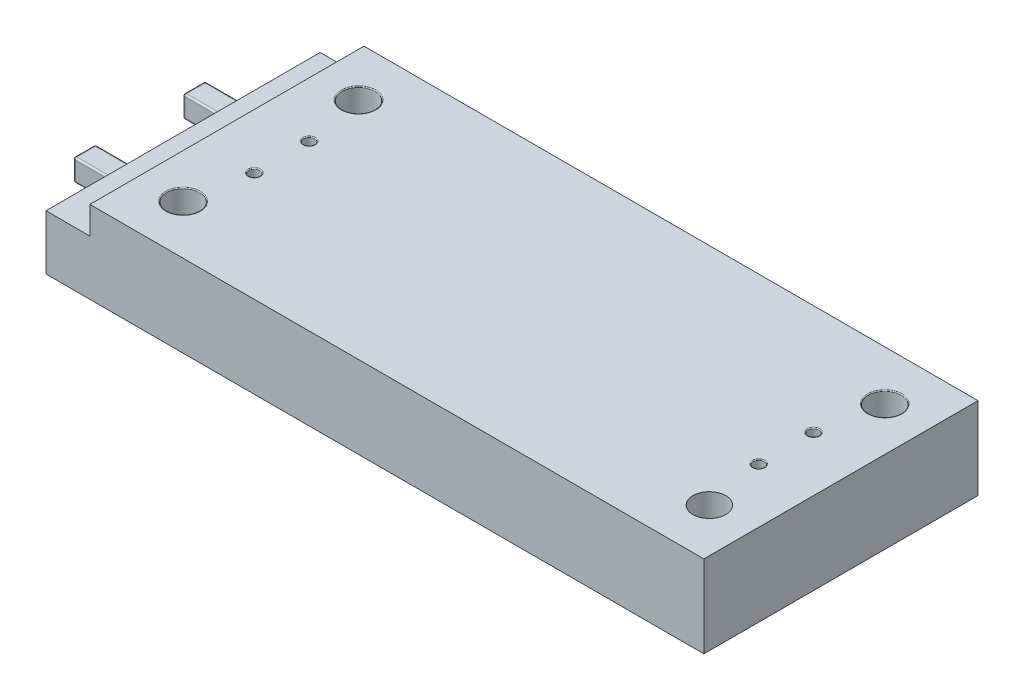
SolidWorks part; units mm, degrees
material "ABS"
ref_plane "Front Plane" through (0, 0, 0) normal (0, 0, 1) x (1, 0, 0)
ref_plane "Top Plane" through (0, 0, 0) normal (0, 1, 0) x (1, 0, 0)
ref_plane "Right Plane" through (0, 0, 0) normal (1, 0, 0) x (0, 0, -1)
sketch "Sketch1" plane through (0, 0, 0) normal (0, 1, 0) x (1, 0, 0)
  line L1 (0, 0) -> (177.8, 0)
  line L2 (0, 0) -> (0, 79.375)
  line L3 (0, 79.375) -> (177.8, 79.375)
  line L4 (177.8, 0) -> (177.8, 79.375)
  dimension "D1" = 177.8
  dimension "D2" = 79.375
extrude "Boss-Extrude1" add sketch "Sketch1" along normal blind 23.8125
sketch "Sketch2" plane through (0, 23.8125, 0) normal (0, 1, 0) x (1, 0, 0)
  line L0 (0, 39.6875) -> (177.8, 39.6875) construction
  line L1 (0, 79.375) -> (0, 0) construction
  line L2 (177.8, 0) -> (177.8, 79.375) construction
  line L3 (88.9, 79.375) -> (88.9, 0) construction
  line L4 (177.8, 79.375) -> (0, 79.375) construction
  line L5 (0, 0) -> (177.8, 0) construction
  circle A0 centre (12.7, 65.0875) radius 4.7625
  circle A1 centre (12.7, 14.2875) radius 4.7625
  circle A2 centre (165.1, 14.2875) radius 4.7625
  circle A3 centre (165.1, 65.0875) radius 4.7625
  dimension "D2" = 9.525
  dimension "D1" = 50.8
  dimension "D3" = 12.7
extrude "Cut-Extrude1" cut sketch "Sketch2" against normal blind 12.7
sketch "Sketch3" plane through (0, 11.1125, 0) normal (0, 1, 0) x (1, 0, 0)
  line L0 (0, 39.6875) -> (177.8, 39.6875) construction
  line L1 (0, 79.375) -> (0, 0) construction
  line L2 (177.8, 0) -> (177.8, 79.375) construction
  line L3 (88.9, 79.375) -> (88.9, 0) construction
  line L4 (0, 0) -> (177.8, 0) construction
  line L5 (177.8, 79.375) -> (0, 79.375) construction
  circle A0 centre (12.7, 65.0875) radius 3.5719
  circle A1 centre (12.7, 14.2875) radius 3.5719
  circle A2 centre (165.1, 14.2875) radius 3.5719
  circle A3 centre (165.1, 65.0875) radius 3.5719
  dimension "D1" = 7.1437
extrude "Cut-Extrude2" cut sketch "Sketch3" against normal up to surface (11.1125 mm away) up to face at (88.9, 0, -39.6875)
sketch "Sketch4" plane through (0, 0, 0) normal (0, -1, 0) x (1, 0, 0)
  line L0 (0, -39.6875) -> (177.8, -39.6875) construction
  line L1 (0, -79.375) -> (0, 0) construction
  line L2 (177.8, 0) -> (177.8, -79.375) construction
  line L3 (88.9, 0) -> (88.9, -79.375) construction
  line L4 (0, 0) -> (177.8, 0) construction
  line L5 (177.8, -79.375) -> (0, -79.375) construction
  circle A0 centre (15.875, -31.75) radius 2.7781
  circle A1 centre (15.875, -47.625) radius 2.7781
  circle A2 centre (161.925, -47.625) radius 2.7781
  circle A3 centre (161.925, -31.75) radius 2.7781
  dimension "D1" = 5.5562
  dimension "D2" = 15.875
  dimension "D3" = 15.875
extrude "Cut-Extrude3" cut sketch "Sketch4" against normal offset from surface (18.7325 mm away) 5.08 up to face at (165.1, 23.8125, -69.85)
sketch "Sketch10" plane through (0, 18.7325, 0) normal (0, -1, 0) x (1, 0, 0)
  line L0 (0, -39.6875) -> (177.8, -39.6875) construction
  line L1 (0, -79.375) -> (0, 0) construction
  line L2 (177.8, 0) -> (177.8, -79.375) construction
  line L3 (88.9, -79.375) -> (88.9, 0) construction
  line L4 (177.8, -79.375) -> (0, -79.375) construction
  line L5 (0, 0) -> (177.8, 0) construction
  circle A0 centre (15.875, -31.75) radius 1.5875
  circle A1 centre (15.875, -47.625) radius 1.5875
  circle A2 centre (161.925, -47.625) radius 1.5875
  circle A3 centre (161.925, -31.75) radius 1.5875
  dimension "D1" = 3.175
extrude "Cut-Extrude4" cut sketch "Sketch10" against normal up to next
fillet "Fillet1" radius 0.254 15 edges at (12.7, 23.8125, -9.525) (12.7, 23.8125, -60.325) (165.1, 23.8125, -69.85) (12.7, 11.1125, -61.5156) (12.7, 11.1125, -17.8594) (165.1, 11.1125, -10.7156) (165.1, 11.1125, -68.6594) (161.925, 18.7325, -30.1625) (161.925, 18.7325, -49.2125) (15.875, 18.7325, -46.0375) (15.875, 18.7325, -33.3375) (161.925, 23.8125, -49.2125) (161.925, 23.8125, -33.3375) (15.875, 23.8125, -49.2125) (15.875, 23.8125, -33.3375)
sketch "Sketch9" plane through (0, 0, 0) normal (-1, 0, 0) x (0, 0, 1)
  line L0 (-79.375, 23.8125) -> (-79.375, 0) construction
  line L1 (0, 0) -> (-79.375, 0)
  line L2 (0, 0) -> (0, 15.875)
  line L3 (0, 15.875) -> (-79.375, 15.875)
  line L4 (-79.375, 0) -> (-79.375, 15.875)
  dimension "D1" = 15.875
extrude "Boss-Extrude3" add sketch "Sketch9" along normal blind 12.7
sketch "Sketch11" plane through (-12.7, 0, 0) normal (-1, 0, 0) x (0, 0, 1)
  line L0 (-39.6875, 0) -> (-39.6875, 50000) construction
  line L1 (-79.375, 0) -> (0, 0) construction
  line L2 (-58.7375, 12.7) -> (-58.7375, 6.35)
  line L3 (-26.9875, 12.7) -> (-20.6375, 12.7)
  line L4 (-26.9875, 12.7) -> (-26.9875, 6.35)
  line L5 (-26.9875, 6.35) -> (-20.6375, 6.35)
  line L6 (-20.6375, 12.7) -> (-20.6375, 6.35)
  line L7 (-52.3875, 6.35) -> (-58.7375, 6.35)
  line L8 (-52.3875, 12.7) -> (-52.3875, 6.35)
  line L9 (-52.3875, 12.7) -> (-58.7375, 12.7)
  point P4 (-39.6875, 0)
  dimension "D1" = 12.7
  dimension "D2" = 6.35
  dimension "D3" = 6.35
extrude "Boss-Extrude4" add sketch "Sketch11" along normal blind 12.7
fillet "Fillet2" radius 0.508 16 edges at (-25.4, 12.7, -23.8125) (-25.4, 9.525, -20.6375) (-25.4, 6.35, -23.8125) (-25.4, 9.525, -26.9875) (-25.4, 9.525, -52.3875) (-25.4, 6.35, -55.5625) (-25.4, 9.525, -58.7375) (-25.4, 12.7, -55.5625) (-19.05, 6.35, -20.6375) (-19.05, 12.7, -20.6375) (-19.05, 6.35, -26.9875) (-19.05, 12.7, -26.9875) (-19.05, 6.35, -58.7375) (-19.05, 6.35, -52.3875) (-19.05, 12.7, -58.7375) (-19.05, 12.7, -52.3875)
